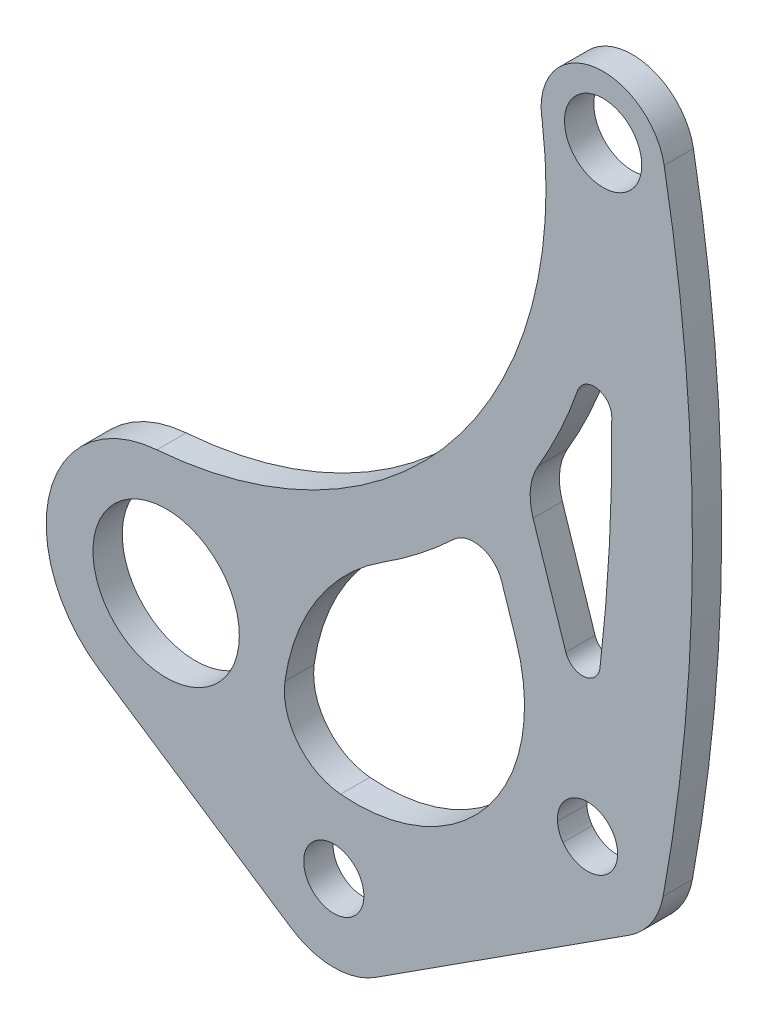
SolidWorks part; units mm, degrees
material "6061-T6 (SS)"
ref_plane "Front Plane" through (0, 0, 0) normal (0, 0, 1) x (1, 0, 0)
ref_plane "Top Plane" through (0, 0, 0) normal (0, 1, 0) x (1, 0, 0)
ref_plane "Right Plane" through (0, 0, 0) normal (1, 0, 0) x (0, 0, -1)
sketch "Sketch2" plane through (0, 0, 0) normal (0, 0, 1) x (1, 0, 0)
  line L0 (0, 0) -> (45.72, 0) construction
  line L1 (45.72, 0) -> (47.4133, 66.0183) construction
  line L2 (47.4133, 66.0183) -> (0, 0) construction
  line L3 (-9.9543, 8.3886) -> (42.2663, 70.3558)
  line L4 (54.1443, 66.0101) -> (54.0639, -0.0102)
  line L5 (46.5729, -8.3002) -> (1.3307, -12.9493)
  line L6 (-6.2268, 4.9225) -> (44.1256, 68.6173)
  line L7 (0.8114, -7.8959) -> (46.0536, -3.2468)
  line L8 (48.9813, -0.1295) -> (51.601, 65.852)
  line L9 (0, 0) -> (18.1918, -17.7262) construction
  line L10 (45.72, 0) -> (38.8832, 9.7026) construction
  line L11 (45.72, 0) -> (42.0108, 11.275) construction
  line L12 (45.72, 0) -> (44.9726, 11.8459) construction
  line L13 (47.2407, 59.2895) -> (45.9339, 8.3412)
  line L14 (45.72, 0) -> (36.8585, 26.9366) construction
  line L15 (34.7499, 24.3546) -> (40.5957, 6.585)
  line L16 (38.8824, 29.7758) -> (45.9339, 8.3412)
  line L17 (41.2892, 13.4683) -> (38.6201, 12.5902) construction
  line L18 (41.2892, 13.4683) -> (43.9584, 14.3464) construction
  line L19 (0, 0) -> (18.1918, -17.7262) construction
  line L20 (-7.2141, -10.8357) -> (13.5678, -24.6716)
  line L21 (50.2373, -7.0153) -> (22.7092, -24.7415)
  line L22 (10.645, 7.4925) -> (25.015, -12.9236)
  line L23 (41.2027, 7.0153) -> (13.6745, -10.7109)
  line L26 (237.1837, -665.5499) -> (-723.8072, 270.8428) construction
  circle A0 centre (0, 0) radius 7.9375
  circle A1 centre (45.72, 0) radius 3.2639
  circle A2 centre (47.4133, 66.0183) radius 4.191
  circle A3 centre (0, 0) radius 13.0175
  circle A4 centre (45.72, 0) radius 8.3439
  circle A5 centre (47.4133, 66.0183) radius 6.731
  circle A8 centre (-4.5053, 58.5645) radius 45.72
  circle A9 centre (-4.5053, 58.5645) radius 52.07
  circle A10 centre (-133.3933, 33.155) radius 190.5
  circle A11 centre (-142.1385, 38.656) radius 190.5
  circle A13 centre (18.1918, -17.7262) radius 3.2639
  circle A14 centre (18.1918, -17.7262) radius 8.3439
  point P29 (47.2407, 59.2895)
  point P30 (45.72, 0)
  dimension "D1" = 8.382
  dimension "D2" = 6.5278
  dimension "D3" = 15.875
  dimension "D13" = 381
  dimension "D14" = 381
  dimension "D17" = 91.44
  dimension "D19" = 6.5278
  dimension "2.7" = 45.72
  dimension "D5" = 66.04
  dimension "D6" = 5.08
  dimension "D7" = 2.54
  dimension "D8" = 5.08
  dimension "D9" = 81.28
  dimension "D4" = 54.83
  dimension "D10" = 71.79
  dimension "D11" = 86.39
  dimension "D12" = 6.35
  dimension "D15" = 25.4
  dimension "D18" = 5.08
extrude "Boss-Extrude1" add sketch "Sketch2" along normal blind 3.175 contours A4 L23 L15 | A9 A2 L8 A5 | A9 A5 L8 A2 | A11 A5 A9 A2 | A5 A11 A2 L6 | A2 A11 A5 L6 | A11 A2 A9 A5 | A11 A4 L8 A5 A9 | A5 L8 A4 L4 | A4 A10 A5 L4 | A11 A4 L8 A1 L7 | A11 A1 L8 A4 | L7 A11 A1 A4 | A4 A11 L7 | A11 L7 A1 | A14 L21 A11 L5 L22 | A14 L5 A13 | L5 A14 | A14 L5 L22 L23 | A14 L22 L5 | L5 A11 A4 L7 L23 L22 | A11 L5 A4 | A11 L21 A4 L5 | A14 L5 A3 L20 | A14 L23 L22 L7 A3 L5 | A9 A3 L7 A0 L6 | A3 A9 L6 | L6 A9 A0 A3 | A9 L6 A0 | A9 A0 L7 A3 | A4 L15 L23 L7 | A9 L15 L23 A4 L16 | A3 A9 L13 A5 L6 A8 | A11 A9 A5 | A9 A11 L13 | L23 L7 L22 | A8 A3 L6
ref_plane "Plane2" through (45.72, 0, 0) normal (-0.576, 0.8174, 0) x (0.8174, 0.576, 0)
split line "Split Line2"
ref_plane "Plane3" through (45.72, 0, 0) normal (-0.063, 0.998, 0) x (0.998, 0.063, 0)
split line "Split Line3"
fillet "Fillet1" [suppressed] radius 2.54
fillet "Fillet2" [suppressed] radius 3.81
fillet "Fillet3" radius 1.905 2 edges at (45.9339, 8.3412, 1.5875) (47.5238, 56.5014, 1.5875)
fillet "Fillet4" radius 6.35 1 edges at (38.8824, 29.7758, 1.5875)
sketch "Sketch3" plane through (0, 0, 3.175) normal (0, 0, 1) x (1, 0, 0)
  line L0 (0, 0) -> (18.1918, -17.7262) construction
  line L1 (34.7499, 24.3546) -> (40.585, 6.6176) construction
  line L2 (18.1918, -17.7262) -> (45.72, 0) construction
  circle A0 centre (45.72, 0) radius 8.3439
  circle A1 centre (18.1918, -17.7262) radius 8.3439
  circle A2 centre (0, 0) radius 13.0175
  circle A3 centre (0, 0) radius 7.9375 construction
  circle A4 centre (18.1918, -17.7262) radius 3.2639 construction
  arc A5 (48.3881, 1.88) -> (42.4626, -0.2055) centre (45.72, 0) ccw construction
  circle A7 centre (20.5527, 8.8458) radius 18.3327
  circle A9 centre (19.523, -2.744) radius 6.6973
  circle A11 centre (36.0489, -5.0667) radius 23.3857
  arc A12 (9.8489, 8.5121) -> (34.7499, 24.3546) centre (-4.5053, 58.5645) ccw construction
  line M20 (21.3187, -5.7886) -> (11.0749, -6.8412)
  arc M21 (11.0749, -6.8412) -> (9.8489, 8.5121) centre (0, 0) ccw
  arc M22 (9.8489, 8.5121) -> (34.7499, 24.3546) centre (-4.5053, 58.5645) ccw
  line M23 (34.7499, 24.3546) -> (40.585, 6.6176)
  line M24 (40.585, 6.6176) -> (21.3187, -5.7886)
  dimension "D1" = 5.08
  dimension "D2" = 5.08
  dimension "D3" = 5.08
extrude "Boss-Extrude2" add sketch "Sketch3" against normal blind 3.175 contours A7 M24 M23 | A9 M21 M20 | A9 A11 M20 | A11 A2 M22
sketch "Sketch4" plane through (0, 0, 0) normal (0, 0, 1) x (1, 0, 0)
  line L0 (0, 0) -> (18.1918, -17.7262) construction
  line L1 (34.7499, 24.3546) -> (37.9672, 14.5748) construction
  line L2 (18.1918, -17.7262) -> (45.72, 0) construction
  line L3 (12.8908, -1.8118) -> (38.5393, 5.3003)
  line L4 (38.5393, 5.3003) -> (21.3187, -5.7886) construction
  circle A0 centre (45.72, 0) radius 8.3439
  circle A1 centre (18.1918, -17.7262) radius 8.3439
  circle A2 centre (0, 0) radius 13.0175
  circle A7 centre (20.5527, 8.8458) radius 18.3327
  circle A9 centre (19.523, -2.744) radius 6.6973
  circle A10 centre (0, 0) radius 7.9375 construction
  circle A11 centre (18.1918, -17.7262) radius 3.2639 construction
  arc A12 (48.3881, 1.88) -> (42.4626, -0.2055) centre (45.72, 0) ccw construction
  dimension "D1" = 5.08
  dimension "D2" = 5.08
  dimension "D3" = 5.08
extrude "Cut-Extrude1" cut sketch "Sketch4" along normal blind 12.065 contours A9 A7 L3 | L3 A9
fillet "Fillet5" radius 3.175 1 edges at (34.7499, 24.3546, 1.5875)
equation "\"Droop angle\"= 54.83"
equation "\"Static angle\"= 71.79"
equation "\"Jounce angle\"= 86.39"
equation "\"D4@Sketch2\"=\"Droop angle\""
equation "\"D10@Sketch2\"=\"Static angle\""
equation "\"D11@Sketch2\"=\"Jounce angle\""
equation "\"DL Rocker Angle\"= 50.124deg"
equation "\"DL Rocker Length\"= 1.0in"
equation "\"D15@Sketch2\"=\"DL Rocker Length\""
